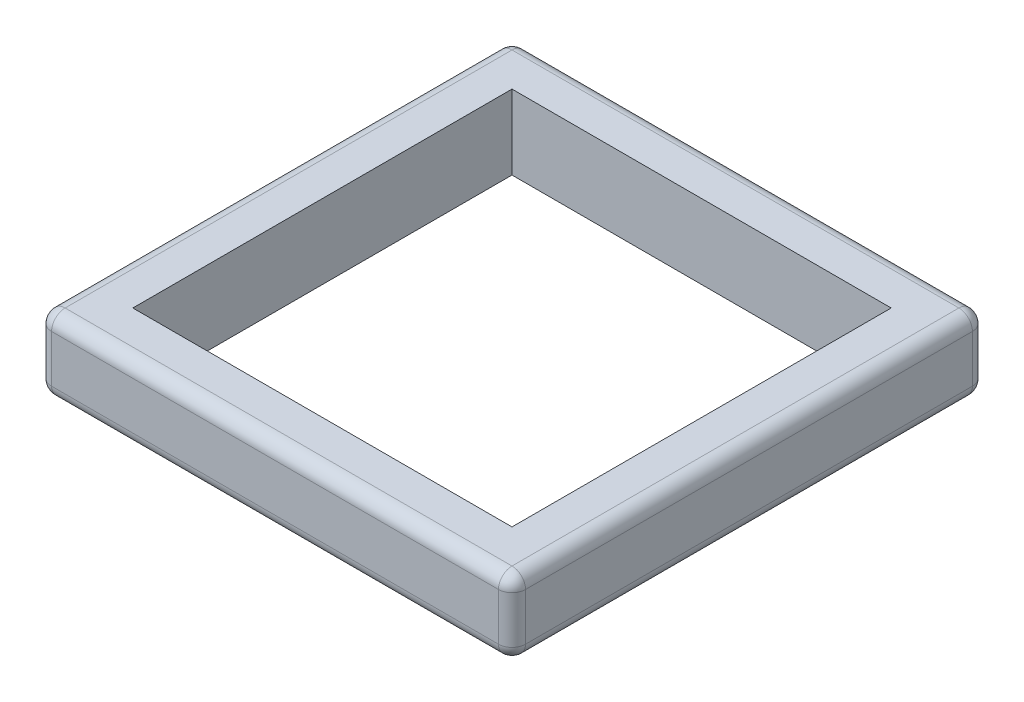
SolidWorks part; units mm, degrees
ref_plane "Front Plane" through (0, 0, 0) normal (0, 0, 1) x (1, 0, 0)
ref_plane "Top Plane" through (0, 0, 0) normal (0, 1, 0) x (1, 0, 0)
ref_plane "Right Plane" through (0, 0, 0) normal (1, 0, 0) x (0, 0, -1)
sketch "Sketch1" plane through (0, 0, 0) normal (0, 1, 0) x (1, 0, 0)
  line L1 (-394.3109, -376.7559) -> (316.8891, -376.7559)
  line L2 (-394.3109, -376.7559) -> (-394.3109, 334.4441)
  line L3 (-394.3109, 334.4441) -> (316.8891, 334.4441)
  line L4 (316.8891, -376.7559) -> (316.8891, 334.4441)
  line L5 (-394.3109, -376.7559) -> (316.8891, 334.4441) construction
  line L6 (-394.3109, 334.4441) -> (316.8891, -376.7559) construction
  line L7 (-483.2109, -465.6559) -> (405.7891, -465.6559)
  line L8 (-483.2109, -465.6559) -> (-483.2109, 423.3441)
  line L9 (-483.2109, 423.3441) -> (405.7891, 423.3441)
  line L10 (405.7891, -465.6559) -> (405.7891, 423.3441)
  line L11 (-483.2109, -465.6559) -> (405.7891, 423.3441) construction
  line L12 (-483.2109, 423.3441) -> (405.7891, -465.6559) construction
  point P0 (-38.7109, -21.1559)
  point P5 (-38.7109, -21.1559)
  dimension "D1" = 711.2
  dimension "D2" = 711.2
  dimension "D3" = 88.9
  dimension "D4" = 88.9
extrude "Boss-Extrude1" add sketch "Sketch1" along normal blind 139.7
fillet "Fillet2" radius 25.4 12 edges at (405.7891, 69.85, 465.6559) (-483.2109, 69.85, 465.6559) (405.7891, 69.85, -423.3441) (-483.2109, 69.85, -423.3441) (-483.2109, 0, 21.1559) (-38.7109, 0, -423.3441) (-483.2109, 139.7, 21.1559) (-38.7109, 139.7, -423.3441) (-38.7109, 0, 465.6559) (405.7891, 0, 21.1559) (405.7891, 139.7, 21.1559) (-38.7109, 139.7, 465.6559)
